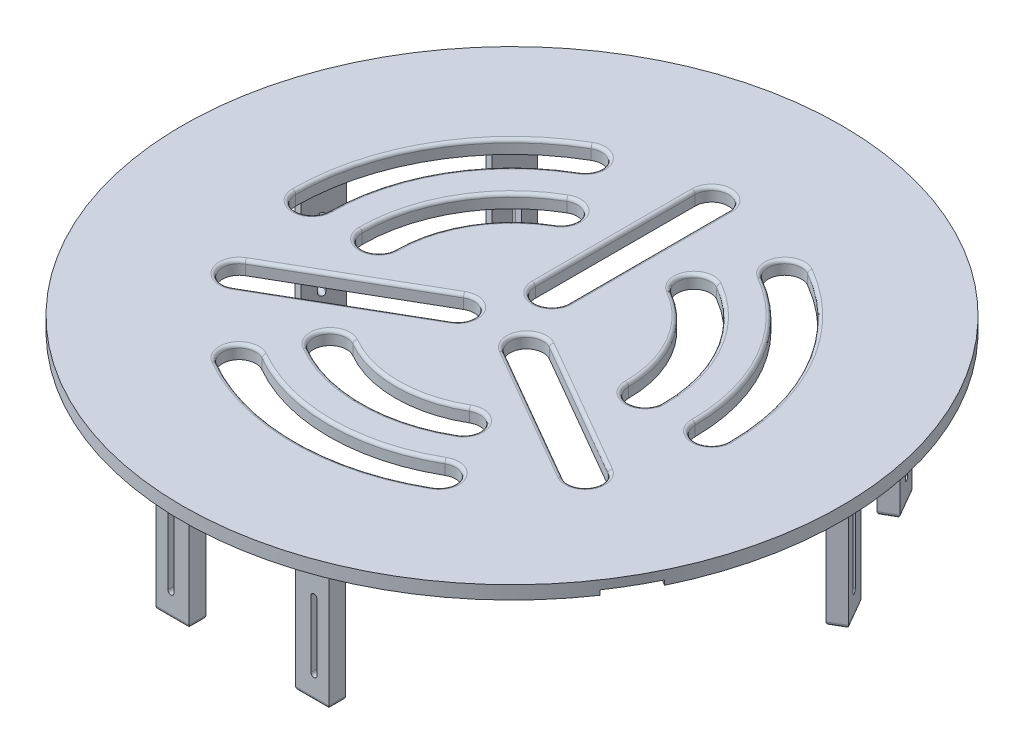
SolidWorks part; units mm, degrees
ref_plane "前视基准面" through (0, 0, 0) normal (0, 0, 1) x (1, 0, 0)
ref_plane "上视基准面" through (0, 0, 0) normal (0, 1, 0) x (1, 0, 0)
ref_plane "右视基准面" through (0, 0, 0) normal (1, 0, 0) x (0, 0, -1)
other "Configuration Table"
sketch "草图1" plane through (0, 0, 0) normal (0, 1, 0) x (1, 0, 0)
  circle A0 centre (0, 0) radius 99
  dimension "D1" = 198
extrude "凸台-拉伸1" add sketch "草图1" along normal blind 4
sketch "草图6" plane through (0, 0, 0) normal (0, 1, 0) x (1, 0, 0)
  line L0 (0, 0) -> (0, 100) construction
  line L1 (-7.1, 100) -> (7.1, 100)
  line L2 (7.1, 100) -> (7.1, 74)
  line L3 (7.1, 74) -> (-7.1, 74)
  line L4 (-7.1, 100) -> (-7.1, 74)
  point P10 (0, 74)
  dimension "D1" = 100
  dimension "D2" = 7.1
  dimension "D3" = 26
extrude "切除-拉伸1" cut sketch "草图6" along normal blind 1.4
pattern_circular "阵列(圆周)1" count 3 every 120 about axis through (0, 0, 0) along (0, 1, 0) of "切除-拉伸1"
sketch "草图7" plane through (0, 0, 0) normal (0, 1, 0) x (1, 0, 0)
  line L0 (0, -90) -> (0, 0) construction
  line L1 (-26, -99) -> (26, -99) construction
  line L2 (-26, -99) -> (-26, -81) construction
  line L3 (-26, -81) -> (26, -81) construction
  line L4 (26, -99) -> (26, -81) construction
  line L5 (-26, -99) -> (26, -81) construction
  line L6 (-26, -81) -> (26, -99) construction
  line L7 (-26, -81) -> (-16, -81)
  line L8 (-26, -81) -> (-16, -81) construction
  line L9 (-26, -81) -> (-26, -76)
  line L10 (-26, -76) -> (-16, -76)
  line L11 (-16, -81) -> (-16, -76)
  line L12 (26, -81) -> (16, -81) construction
  line L13 (16, -81) -> (16, -76)
  line L14 (26, -76) -> (16, -76)
  line L15 (26, -81) -> (26, -76)
  line L16 (26, -81) -> (16, -81)
  point P0 (0, -90)
  dimension "D1" = 52
  dimension "D2" = 18
  dimension "D3" = 90
  dimension "D4" = 5
  dimension "D5" = 10
extrude "凸台-拉伸2" add sketch "草图7" against normal blind 45
sketch "草图8" plane through (0, 0, 0) normal (0, 0, 1) x (1, 0, 0)
  line L0 (-21.5, -18) -> (-21.5, -38) construction
  line L1 (-20.6, -18) -> (-20.6, -38)
  line L2 (-22.4, -18) -> (-22.4, -38)
  line L5 (0, 0) -> (0, -29.6035) construction
  line L6 (21.5, -18) -> (21.5, -38) construction
  line L7 (20.6, -18) -> (20.6, -38)
  line L8 (22.4, -18) -> (22.4, -38)
  circle A0 centre (-21.1805, -19.4514) radius 0.8 construction
  circle A1 centre (21.6395, -19.4514) radius 0.8 construction
  circle A2 centre (21.6395, -1.7114) radius 0.8 construction
  circle A3 centre (-21.1805, -1.7114) radius 0.8 construction
  arc A4 (-20.6, -18) -> (-22.4, -18) centre (-21.5, -18) ccw
  arc A5 (-22.4, -38) -> (-20.6, -38) centre (-21.5, -38) ccw
  arc A6 (20.6, -18) -> (22.4, -18) centre (21.5, -18) cw
  arc A7 (22.4, -38) -> (20.6, -38) centre (21.5, -38) cw
  point P10 (-21.5, -28)
  point P20 (21.5, -28)
  dimension "D4" = 38
  dimension "D1" = 1.8
  dimension "D2" = 20
  dimension "D3" = 21.5
extrude "切除-拉伸2" cut sketch "草图8" along normal through all
chamfer "倒角1" distance 5 angle 45 8 edges at (-21, 0, 81) (21, 0, 81) (-16, 0, 78.5) (-21, 0, 76) (-26, 0, 78.5) (21, 0, 76) (26, 0, 78.5) (16, 0, 78.5)
fillet "圆角1" radius 1 8 edges at (-21, -45, 81) (-16, -45, 78.5) (-21, -45, 76) (-26, -45, 78.5) (26, -45, 78.5) (21, -45, 76) (16, -45, 78.5) (21, -45, 81)
pattern_circular "阵列(圆周)2" count 3 every 120 about axis through (0, 0, 0) along (0, 1, 0) of "倒角1", "切除-拉伸2", "凸台-拉伸2", "圆角1"
sketch "草图11" plane through (0, 0, 0) normal (0, 1, 0) x (1, 0, 0)
  line L0 (0, 12) -> (0, 60) construction
  line L1 (-5, 12) -> (-5, 60)
  line L2 (5, 12) -> (5, 60)
  line L3 (-60, 0) -> (0, 0) construction
  line L4 (7.8923, -10.3301) -> (49.4615, -34.3301)
  line L5 (12.8923, -1.6699) -> (54.4615, -25.6699)
  line L6 (10.3923, -6) -> (51.9615, -30) construction
  line L7 (-12.8923, -1.6699) -> (-54.4615, -25.6699)
  line L8 (-7.8923, -10.3301) -> (-49.4615, -34.3301)
  line L9 (-10.3923, -6) -> (-51.9615, -30) construction
  arc A0 (-5, 12) -> (5, 12) centre (0, 12) ccw
  arc A1 (5, 60) -> (-5, 60) centre (0, 60) ccw
  arc A2 (-30, 51.9615) -> (-60, 0) centre (0, 0) ccw construction
  arc A3 (-32.5, 56.2917) -> (-65, 0) centre (0, 0) ccw
  arc A4 (-27.5, 47.6314) -> (-55, 0) centre (0, 0) ccw
  arc A5 (-27.5, 47.6314) -> (-32.5, 56.2917) centre (-30, 51.9615) ccw
  arc A6 (-65, 0) -> (-55, 0) centre (-60, 0) ccw
  arc A7 (-20, 34.641) -> (-40, 0) centre (0, 0) ccw construction
  arc A8 (-22.4999, 38.9711) -> (-44.9999, 0) centre (0, 0) ccw
  arc A9 (-17.5001, 30.311) -> (-35.0001, 0) centre (0, 0) ccw
  arc A10 (-17.5001, 30.311) -> (-22.4999, 38.9711) centre (-20, 34.641) ccw
  arc A11 (-44.9999, 0) -> (-35.0001, 0) centre (-40, 0) ccw
  arc A12 (55, 0) -> (27.5, 47.6314) centre (0, 0) ccw
  arc A13 (55, 0) -> (65, 0) centre (60, 0) ccw
  arc A14 (32.5, 56.2917) -> (27.5, 47.6314) centre (30, 51.9615) ccw
  arc A15 (65, 0) -> (32.5, 56.2917) centre (0, 0) ccw
  arc A16 (12.8923, -1.6699) -> (7.8923, -10.3301) centre (10.3923, -6) ccw
  arc A17 (49.4615, -34.3301) -> (54.4615, -25.6699) centre (51.9615, -30) ccw
  arc A18 (60, 0) -> (30, 51.9615) centre (0, 0) ccw construction
  arc A19 (40, 0) -> (20, 34.641) centre (0, 0) ccw construction
  arc A20 (44.9999, 0) -> (22.4999, 38.9711) centre (0, 0) ccw
  arc A21 (35.0001, 0) -> (17.5001, 30.311) centre (0, 0) ccw
  arc A22 (35.0001, 0) -> (44.9999, 0) centre (40, 0) ccw
  arc A23 (22.4999, 38.9711) -> (17.5001, 30.311) centre (20, 34.641) ccw
  arc A24 (-27.5, -47.6314) -> (27.5, -47.6314) centre (0, 0) ccw
  arc A25 (-27.5, -47.6314) -> (-32.5, -56.2917) centre (-30, -51.9615) ccw
  arc A26 (32.5, -56.2917) -> (27.5, -47.6314) centre (30, -51.9615) ccw
  arc A27 (-32.5, -56.2917) -> (32.5, -56.2917) centre (0, 0) ccw
  arc A28 (-7.8923, -10.3301) -> (-12.8923, -1.6699) centre (-10.3923, -6) ccw
  arc A29 (-54.4615, -25.6699) -> (-49.4615, -34.3301) centre (-51.9615, -30) ccw
  arc A30 (-30, -51.9615) -> (30, -51.9615) centre (0, 0) ccw construction
  arc A31 (-20, -34.641) -> (20, -34.641) centre (0, 0) ccw construction
  arc A32 (-22.4999, -38.9711) -> (22.4999, -38.9711) centre (0, 0) ccw
  arc A33 (-17.5001, -30.311) -> (17.5001, -30.311) centre (0, 0) ccw
  arc A34 (-17.5001, -30.311) -> (-22.4999, -38.9711) centre (-20, -34.641) ccw
  arc A35 (22.4999, -38.9711) -> (17.5001, -30.311) centre (20, -34.641) ccw
  point P3 (0, 36)
  point P8 (-51.9615, 30)
  point P18 (-34.641, 20)
  point P30 (31.1769, -18)
  point P35 (51.9615, 30)
  point P42 (34.641, 20)
  point P51 (-31.1769, -18)
  point P56 (0, -60)
  point P63 (0, -40)
  point P70 (0, 0)
  dimension "D5" = 60
  dimension "D6" = 60
  dimension "D9" = 40
  dimension "D1" = 10
  dimension "D2" = 48
  dimension "D3" = 10
  dimension "D7" = 9.9998
  dimension "D10" = 3
  dimension "D4" = 60
  dimension "D8" = 60
extrude "切除-拉伸5" cut sketch "草图11" along normal blind 10
fillet "圆角2" radius 1 36 edges at (6.0622, 4, 3.5) (28.6769, 4, 22.3301) (56.2917, 4, 32.5) (60, 4, 5) (56.2917, 4, -32.5) (25.6699, 4, -54.4615) (40, 4, 4.9999) (38.9711, 4, -22.4999) (15.67, 4, -37.141) (0, 4, -65) (-5, 4, -36) (0, 4, -7) (-15.67, 4, -37.141) (-38.9711, 4, -22.4999) (-40, 4, 4.9999) (24.33, 4, 32.1411) (0, 4, 35.0001) (-24.33, 4, 32.1411) (-34.3301, 4, 49.4615) (0, 4, 65) (34.3301, 4, 49.4615) (-56.2917, 4, 32.5) (-28.6769, 4, 22.3301) (-6.0622, 4, 3.5) (-60, 4, 5) (-47.6314, 4, -27.5) (-25.6699, 4, -54.4615) (33.6769, 4, 13.6699) (47.6314, 4, -27.5) (30.311, 4, -17.5001) (5, 4, -36) (-30.311, 4, -17.5001) (0, 4, 44.9999) (0, 4, 55) (-33.6769, 4, 13.6699) (-56.2917, 4, -32.5)
